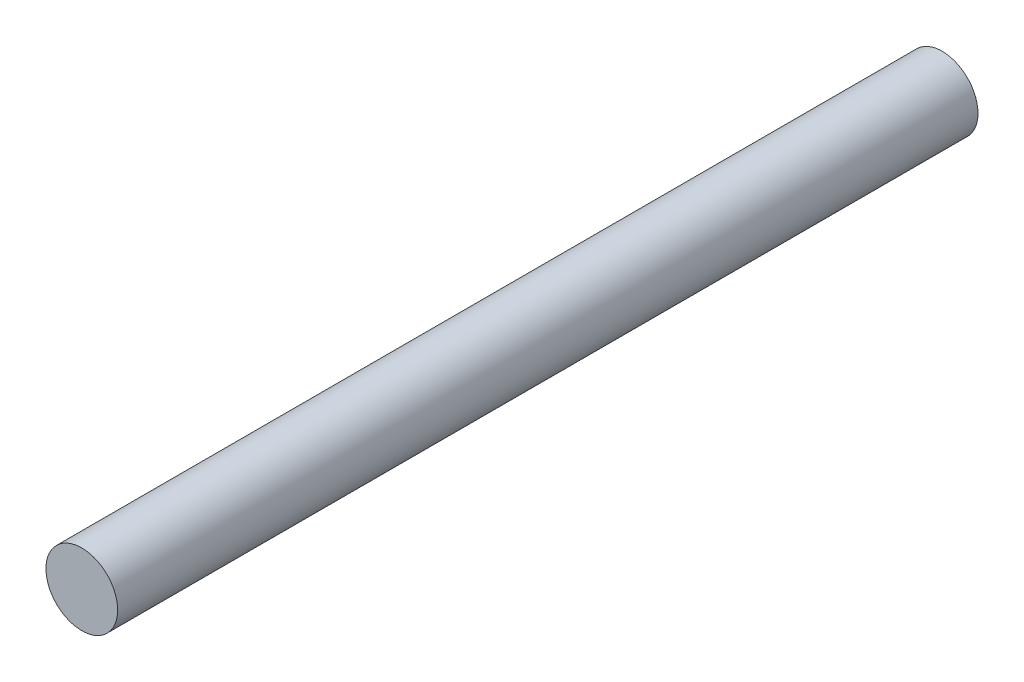
SolidWorks part; units mm, degrees
ref_plane "Plano frontal" through (0, 0, 0) normal (0, 0, 1) x (1, 0, 0)
ref_plane "Plano superior" through (0, 0, 0) normal (0, 1, 0) x (1, 0, 0)
ref_plane "Plano direito" through (0, 0, 0) normal (1, 0, 0) x (0, 0, -1)
sketch "Esboço1" plane through (0, 0, 0) normal (0, 0, 1) x (1, 0, 0)
  circle A0 centre (0, 0) radius 250
  dimension "D1" = 500
extrude "Ressalto-extrusão1" add sketch "Esboço1" along normal blind 6000
